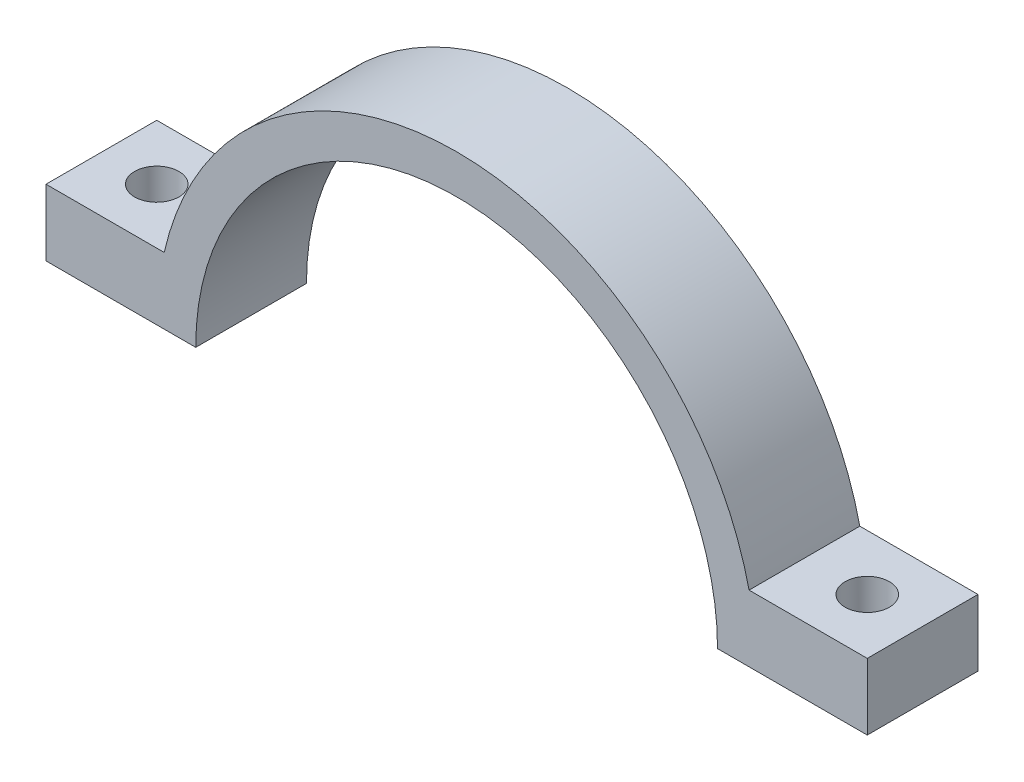
SolidWorks part; units mm, degrees
ref_plane "Front Plane" through (0, 0, 0) normal (0, 0, 1) x (1, 0, 0)
ref_plane "Top Plane" through (0, 0, 0) normal (0, 1, 0) x (1, 0, 0)
ref_plane "Right Plane" through (0, 0, 0) normal (1, 0, 0) x (0, 0, -1)
sketch "Sketch1" plane through (0, 0, 0) normal (0, 0, 1) x (1, 0, 0)
  line L0 (18.54, 0) -> (18.54, 3)
  line L1 (13.54, 0) -> (18.54, 0)
  line L2 (18.54, 3) -> (13.2035, 3)
  line L3 (13.54, 0) -> (11.78, 0)
  line L4 (-11.78, 0) -> (-13.54, 0)
  line L5 (0, 0) -> (0, -5.4819) construction
  line L6 (-13.54, 0) -> (-18.54, 0)
  line L7 (-18.54, 3) -> (-13.2035, 3)
  line L8 (-18.54, 0) -> (-18.54, 3)
  arc A0 (11.78, 0) -> (-11.78, 0) centre (0, 0) ccw
  arc A1 (13.2035, 3) -> (-13.2035, 3) centre (0, 0) ccw
  dimension "D1" = 27.08
  dimension "D2" = 23.56
  dimension "D3" = 5
  dimension "D4" = 3
extrude "Boss-Extrude1" add sketch "Sketch1" along normal blind 5
sketch "Sketch2" plane through (0, 3, 0) normal (0, 1, 0) x (1, 0, 0)
  line L0 (-18.54, 0) -> (-16.04, 0) construction
  line L2 (-13.2035, 0) -> (-18.54, 0) construction
  line L3 (-16.04, 0) -> (-16.04, -2.5) construction
  line L4 (0, 0) -> (0, -12.5557) construction
  circle A0 centre (-16.04, -2.5) radius 1
  circle A1 centre (16.04, -2.5) radius 1
  dimension "D3" = 2
  dimension "D1" = 2.5
  dimension "D2" = 2.5
extrude "Cut-Extrude1" cut sketch "Sketch2" against normal blind 5
